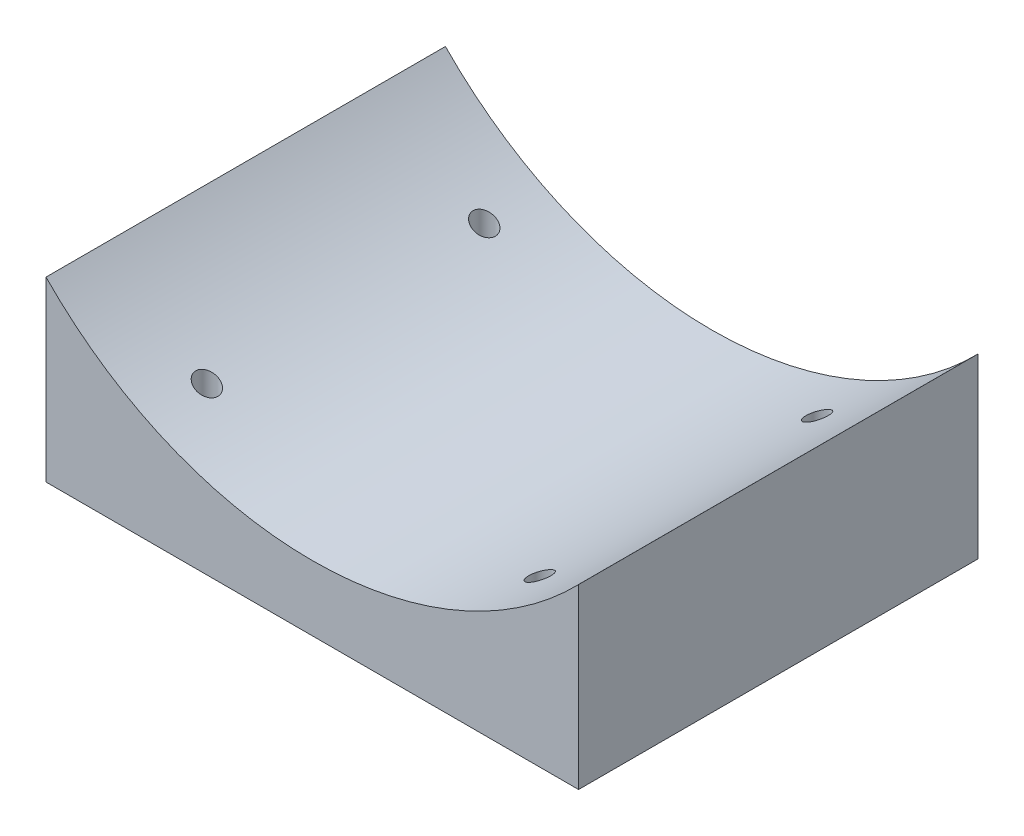
SolidWorks part; units mm, degrees
ref_plane "Front" through (0, 0, 0) normal (0, 0, 1) x (1, 0, 0)
ref_plane "Top" through (0, 0, 0) normal (0, 1, 0) x (1, 0, 0)
ref_plane "Right" through (0, 0, 0) normal (1, 0, 0) x (0, 0, -1)
sketch "Çizim1" plane through (0, 0, 0) normal (0, 0, 1) x (1, 0, 0)
  circle A0 centre (0, 0) radius 148
  circle A1 centre (0, 0) radius 167.5
  dimension "D1" = 296
  dimension "D2" = 335
extrude "Yükseklik-Ekstrüzyon2" add sketch "Çizim1" along normal blind 185.3
sketch "Çizim9" plane through (0, 0, 0) normal (0, 0, -1) x (-1, 0, 0)
  line L1 (-107.3499, 112.5) -> (107.3499, 112.5) construction
  line L2 (-107.3499, 112.5) -> (-107.3499, -112.5) construction
  line L3 (-107.3499, -112.5) -> (107.3499, -112.5) construction
  line L4 (107.3499, 112.5) -> (107.3499, -112.5) construction
  line L5 (-107.3499, 112.5) -> (107.3499, -112.5) construction
  line L6 (-107.3499, -112.5) -> (107.3499, 112.5) construction
  circle A0 centre (0, 0) radius 155.5 construction
  circle A3 centre (0, 0) radius 148 construction
  circle A4 centre (107.3499, -112.5) radius 3.4
  circle A5 centre (-107.3499, -112.5) radius 3.4
  circle A6 centre (-107.3499, 112.5) radius 3.4
  circle A7 centre (107.3499, 112.5) radius 3.4
  dimension "D1" = 7.5
  dimension "D3" = 6.8
  dimension "D2" = 225
extrude "Kes-Ekstrüzyon1" cut sketch "Çizim9" against normal blind 15
sketch "Çizim10" plane through (0, 0, 0) normal (1, 0, 0) x (0, 0, -1)
  line L0 (0, 0) -> (-115.3775, 0) construction
  line L1 (-35, 158.9078) -> (-30, 158.9078)
  line L2 (-35, 158.9078) -> (-35, 142.5)
  line L3 (-35, 142.5) -> (-30, 142.5)
  line L4 (-30, 158.9078) -> (-30, 142.5)
  line L5 (0, -167.5) -> (0, 167.5) construction
  dimension "D1" = 30
  dimension "D2" = 142.5
  dimension "D3" = 5
revolve "Döndür1" add sketch "Çizim10" angle 360 about L0
ref_plane "Düzlem1" through (0, 0, 92.65) normal (0, 0, -1) x (-1, 0, 0)
mirror "Aynalama1" about plane through (0, 0, 92.65) normal (0, 0, -1) of "Kes-Ekstrüzyon1"
sketch "Çizim11" plane through (0, 0, 0) normal (0, 0, 1) x (1, 0, 0)
  line L0 (120, -116.86) -> (120, -200)
  line L1 (120, -200) -> (-120, -200)
  line L2 (-120, -200) -> (-120, -116.86)
  circle A0 centre (0, 0) radius 167.5 construction
  arc A1 (-120, -116.86) -> (120, -116.86) centre (0, 0) ccw
  dimension "D1" = 120
  dimension "D2" = 120
  dimension "D3" = 200
extrude "Yükseklik-Ekstrüzyon3" add sketch "Çizim11" along normal blind 180 separate body
delete or keep bodies "Gövde-Sil/Tut 1" type delete bodies bodies 109
sketch "Çizim12" plane through (0, -200, 0) normal (0, -1, 0) x (1, 0, 0)
  line L0 (-120, 180) -> (120, 180) construction
  line L1 (75, 152.5) -> (-75, 152.5) construction
  line L2 (75, 152.5) -> (75, 27.5) construction
  line L3 (75, 27.5) -> (-75, 27.5) construction
  line L4 (-75, 152.5) -> (-75, 27.5) construction
  line L5 (75, 152.5) -> (-75, 27.5) construction
  line L6 (75, 27.5) -> (-75, 152.5) construction
  line L9 (-120, 180) -> (-120, 0) construction
  circle A0 centre (-75, 152.5) radius 5
  circle A1 centre (75, 152.5) radius 5
  circle A2 centre (75, 27.5) radius 5
  circle A3 centre (-75, 27.5) radius 5
  point P0 (0, 90)
  dimension "D5" = 10
  dimension "D1" = 125
  dimension "D2" = 27.5
  dimension "D3" = 150
  dimension "D4" = 45
sketch "Çizim13" plane through (0, 0, 180) normal (0, 0, 1) x (1, 0, 0)
  line L1 (-160.4267, -196.86) -> (148.2013, -196.86)
  line L2 (-160.4267, -196.86) -> (-160.4267, -250.7513)
  line L3 (-160.4267, -250.7513) -> (148.2013, -250.7513)
  line L4 (148.2013, -196.86) -> (148.2013, -250.7513)
  dimension "D1" = 80
extrude "Kes-Ekstrüzyon2" cut sketch "Çizim13" against normal blind 333
extrude "Kes-Ekstrüzyon3" cut sketch "Çizim12" against normal blind 333
